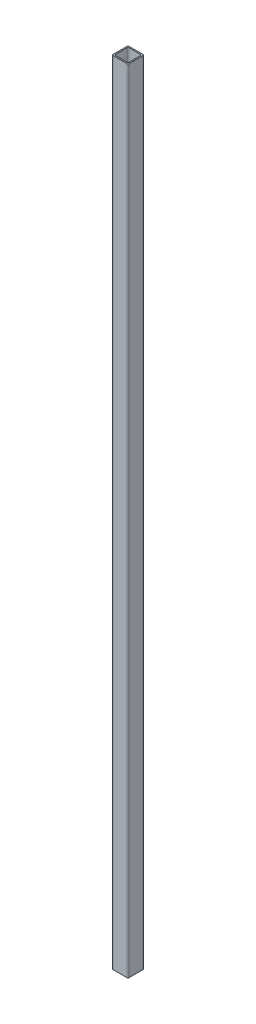
SolidWorks part; units mm, degrees
material "Hexcel AS4C (3000 Filaments)"
ref_plane "Front Plane" through (0, 0, 0) normal (0, 0, 1) x (1, 0, 0)
ref_plane "Top Plane" through (0, 0, 0) normal (0, 1, 0) x (1, 0, 0)
ref_plane "Right Plane" through (0, 0, 0) normal (1, 0, 0) x (0, 0, -1)
sketch "Sketch1" plane through (0, 0, 0) normal (0, 1, 0) x (1, 0, 0)
  line L1 (-9, -10) -> (9, -10)
  line L2 (-10, -9) -> (-10, 9)
  line L3 (-9, 10) -> (9, 10)
  line L4 (10, -9) -> (10, 9)
  line L5 (-10, -10) -> (10, 10) construction
  line L6 (-10, 10) -> (10, -10) construction
  line L7 (-7.5, -8.5) -> (7.5, -8.5)
  line L8 (-8.5, -7.5) -> (-8.5, 7.5)
  line L9 (-7.5, 8.5) -> (7.5, 8.5)
  line L10 (8.5, -7.5) -> (8.5, 7.5)
  line L11 (-8.5, -8.5) -> (8.5, 8.5) construction
  line L12 (-8.5, 8.5) -> (8.5, -8.5) construction
  arc A0 (-9, -10) -> (-10, -9) centre (-9, -9) cw
  arc A1 (9, 10) -> (10, 9) centre (9, 9) cw
  arc A2 (9, -10) -> (10, -9) centre (9, -9) ccw
  arc A3 (-10, 9) -> (-9, 10) centre (-9, 9) cw
  arc A4 (-7.5, -8.5) -> (-8.5, -7.5) centre (-7.5, -7.5) cw
  arc A5 (7.5, -8.5) -> (8.5, -7.5) centre (7.5, -7.5) ccw
  arc A6 (7.5, 8.5) -> (8.5, 7.5) centre (7.5, 7.5) cw
  arc A7 (-8.5, 7.5) -> (-7.5, 8.5) centre (-7.5, 7.5) cw
  point P0 (0, 0)
  point P18 (0, 0)
  dimension "D3" = 1
  dimension "D6" = 1
  dimension "D7" = 1
  dimension "D8" = 1
  dimension "D9" = 1
  dimension "D1" = 20
  dimension "D2" = 20
  dimension "D4" = 17
  dimension "D5" = 17
extrude "Boss-Extrude1" add sketch "Sketch1" along normal blind 1210
sketch "Sketch2" plane through (0, 0, 0) normal (0, -1, 0) x (1, 0, 0)
  line L1 (-46.6317, 52.4419) -> (55.2633, 52.4419)
  line L2 (-46.6317, 52.4419) -> (-46.6317, -85.6856)
  line L3 (-46.6317, -85.6856) -> (55.2633, -85.6856)
  line L4 (55.2633, 52.4419) -> (55.2633, -85.6856)
extrude "Cut-Extrude1" cut sketch "Sketch2" against normal blind 220
